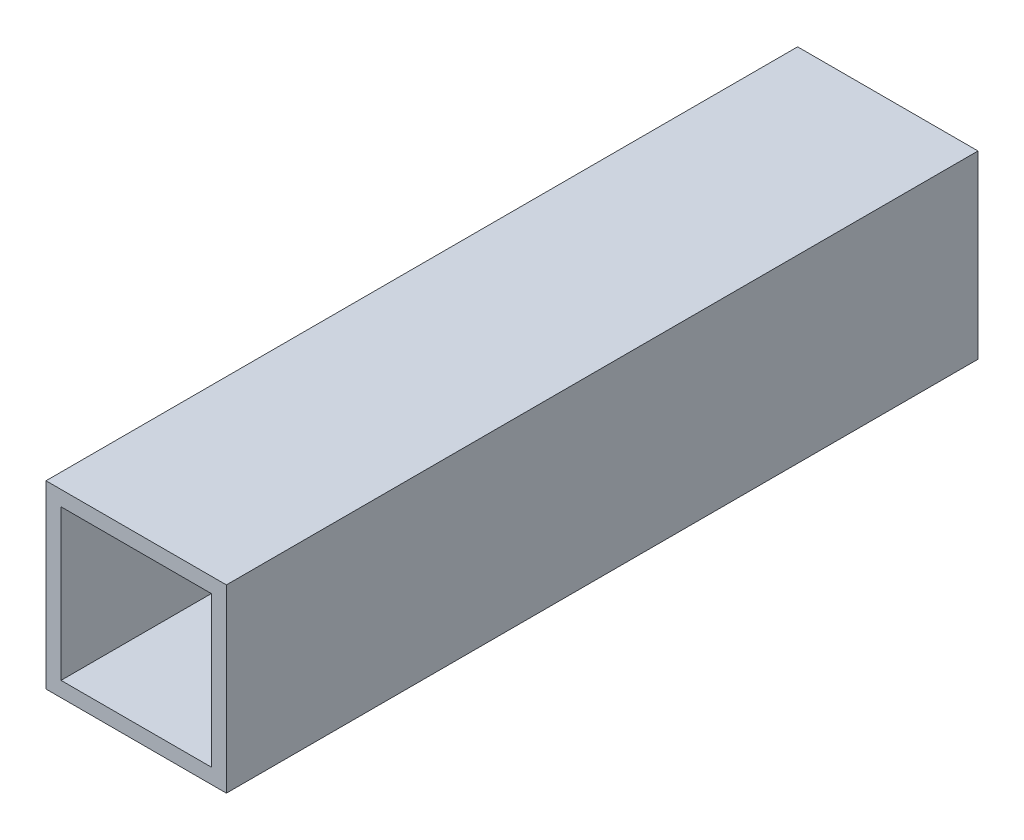
SolidWorks part; units mm, degrees
ref_plane "前视基准面" through (0, 0, 0) normal (0, 0, 1) x (1, 0, 0)
ref_plane "上视基准面" through (0, 0, 0) normal (0, 1, 0) x (1, 0, 0)
ref_plane "右视基准面" through (0, 0, 0) normal (1, 0, 0) x (0, 0, -1)
sketch "草图1" plane through (0, 0, 0) normal (0, 0, 1) x (1, 0, 0)
  line L0 (-12, 12) -> (12, 12)
  line L1 (-10, 10) -> (10, 10)
  line L2 (-10, 10) -> (-10, -10)
  line L3 (-10, -10) -> (10, -10)
  line L4 (10, 10) -> (10, -10)
  line L5 (-10, 10) -> (10, -10) construction
  line L6 (-10, -10) -> (10, 10) construction
  line L7 (12, 12) -> (12, -12)
  line L8 (-12, -12) -> (12, -12)
  line L9 (-12, 12) -> (-12, -12)
  point P0 (0, 0)
  dimension "D1" = 20
  dimension "D2" = 20
  dimension "D3" = 2
extrude "凸台-拉伸1" add sketch "草图1" along normal blind 100
